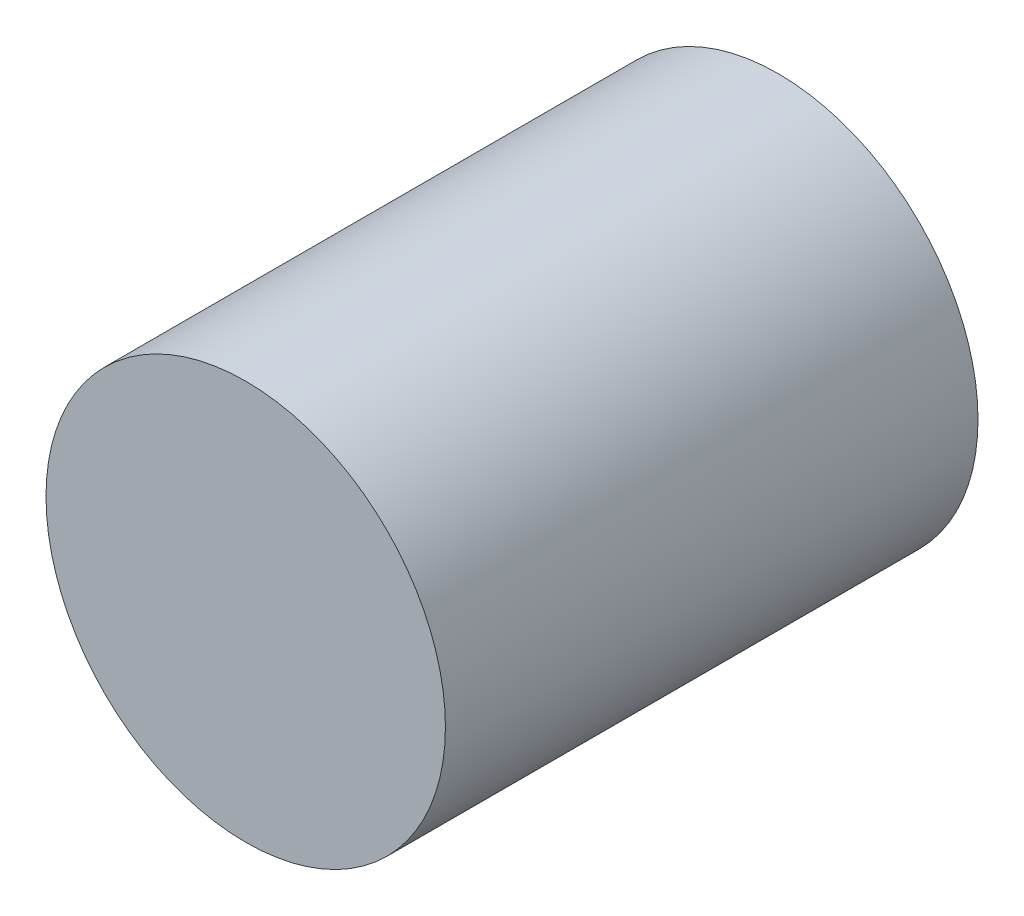
SolidWorks part; units mm, degrees
ref_plane "Front Plane" through (0, 0, 0) normal (0, 0, 1) x (1, 0, 0)
ref_plane "Top Plane" through (0, 0, 0) normal (0, 1, 0) x (1, 0, 0)
ref_plane "Right Plane" through (0, 0, 0) normal (1, 0, 0) x (0, 0, -1)
sketch "Sketch2" plane through (0, 0, 0) normal (0, 0, 1) x (1, 0, 0)
  circle A0 centre (0, 0) radius 6
  dimension "D1" = 12
extrude "Boss-Extrude1" add sketch "Sketch2" along normal blind 16
sketch "Sketch3" plane through (0, 0, 0) normal (0, 0, -1) x (-1, 0, 0)
  circle A0 centre (0, 0) radius 3
extrude "Cut-Extrude1" cut sketch "Sketch3" against normal offset from surface (15.8 mm away) 0.2 up to face at (6, 0, 16)
